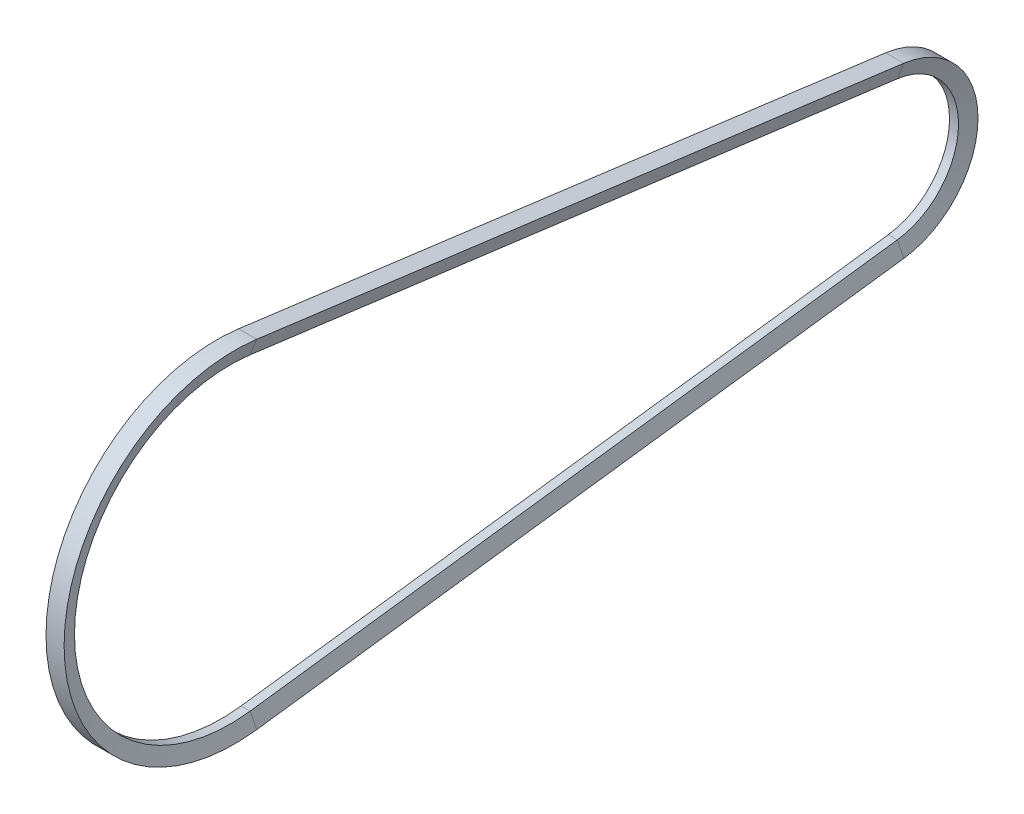
SolidWorks part; units mm, degrees
ref_plane "前视基准面" through (0, 0, 0) normal (0, 0, 1) x (1, 0, 0)
ref_plane "上视基准面" through (0, 0, 0) normal (0, 1, 0) x (1, 0, 0)
ref_plane "右视基准面" through (0, 0, 0) normal (1, 0, 0) x (0, 0, -1)
sketch "草图1" plane through (0, 0, 0) normal (1, 0, 0) x (0, 0, -1)
  line L0 (10.3614, 79.3262) -> (314.0207, 39.6631)
  line L1 (10.3614, -79.3262) -> (314.0207, -39.6631)
  line L2 (0, 0) -> (308.84, 0) construction
  arc A0 (10.3614, 79.3262) -> (10.3614, -79.3262) centre (0, 0) ccw
  arc A1 (314.0207, -39.6631) -> (314.0207, 39.6631) centre (308.84, 0) ccw
  dimension "D1" = 80
  dimension "D2" = 40
  dimension "D3" = 308.84
sketch "草图2" plane through (0, 0, 0) normal (0, 0, 1) x (1, 0, 0)
  line L0 (-4.25, 80) -> (4.25, 80)
  line L1 (4.25, 80) -> (2.1099, 73)
  line L2 (2.1099, 73) -> (-2.1099, 73)
  line L3 (-2.1099, 73) -> (-4.25, 80)
  line L4 (0, 73) -> (0, 80) construction
  line L5 (0, -80) -> (0, 80) construction
  dimension "D1" = 8.5
  dimension "D2" = 7
  dimension "D3" = 34
sweep "扫描1" add profiles "草图2" path "草图1"
equation "\"D3@草图1\" = \"D1@距离1@实心轮_实心轮.Assembly\""
equation "\"D3@草图1\" = \"D1@距离1@实心轮_孔板轮.Assembly\""
equation "\"D3@草图1\" = \"D1@距离1@实心轮_辐板轮.Assembly\""
equation "\"D3@草图1\" = \"D1@距离1@孔板轮_孔板轮.Assembly\""
equation "\"D3@草图1\" = \"D1@距离1@孔板轮_辐板轮.Assembly\""
equation "\"D3@草图1\" = \"D1@距离1@辐板轮_辐板轮.Assembly\""
equation "\"D1@草图2\" = \"bd@草图1@小带轮_实心轮.Part\" "
equation "\"D1@草图2\" = \"bd@草图1@大带轮_孔板轮<1>.Part\""
equation "\"D1@草图2\" = \"bd@草图1@大带轮_辐板轮.Part\" "
equation "\"D2@草图2\" = \"hf@草图1@小带轮_实心轮.Part\" "
equation "\"D2@草图2\" = \"hf@草图1@大带轮_辐板轮.Part\" "
equation "\"D2@草图2\" = \"hf@草图1@大带轮_孔板轮<1>.Part\""
equation "\"D3@草图2\" = \"槽轮角@草图1@小带轮_实心轮.Part\" "
equation "\"D3@草图2\" = \"槽轮角@草图1@大带轮_辐板轮.Part\" "
equation "\"D3@草图2\" = \"槽轮角@草图1@大带轮_孔板轮<1>.Part\""
equation "\"D2@草图1\" = \"dd@草图1@小带轮_实心轮.Part\"/2"
equation "\"D2@草图1\" = \"dd@草图1@小带轮_孔板轮<1>.Part\" / 2"
equation "\"D2@草图1\" = \"dd@草图1@小带轮_辐板轮.Part\"/2  "
equation "\"D1@草图1\" = \"dd@草图1@大带轮_实心轮.Part\" /2"
equation "\"D1@草图1\" = \"dd@草图1@大带轮_孔板轮<1>.Part\" / 2"
equation "\"D1@草图1\" = \"dd@草图1@大带轮_辐板轮.Part\" /2"
